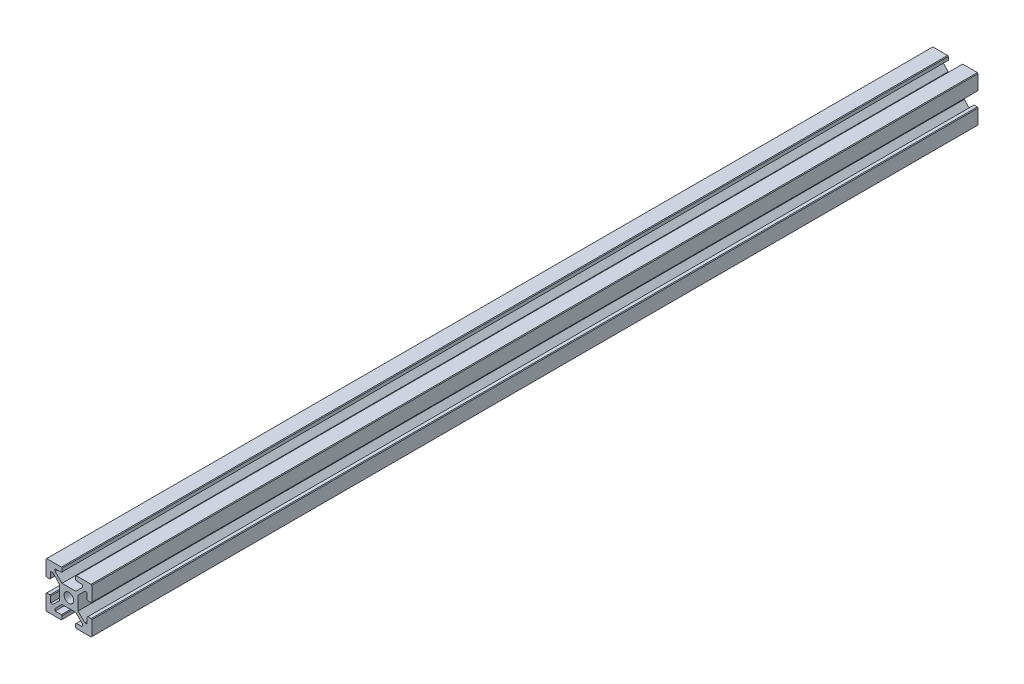
SolidWorks part; units mm, degrees
ref_plane "Front" through (0, 0, 0) normal (0, 0, 1) x (1, 0, 0)
ref_plane "Top" through (0, 0, 0) normal (0, 1, 0) x (1, 0, 0)
ref_plane "Right" through (0, 0, 0) normal (1, 0, 0) x (0, 0, -1)
sketch "Sketch1" plane through (0, 0, 0) normal (0, 0, 1) x (1, 0, 0)
  line L0 (-3, 10) -> (3, 10)
  line L1 (-10, 10) -> (10, 10)
  line L2 (-10, 10) -> (-10, -10)
  line L3 (-10, -10) -> (10, -10)
  line L4 (10, 10) -> (10, -10)
  line L5 (-10, 10) -> (10, -10) construction
  line L6 (-10, -10) -> (10, 10) construction
  line L7 (3, 10) -> (3, 8)
  line L8 (3, 8) -> (6, 8)
  line L9 (-3, 4) -> (3, 4)
  line L10 (0, -11) -> (0, 11) construction
  line L11 (3, 4) -> (6, 7)
  line L12 (6, 7) -> (6, 8)
  line L13 (10, 3) -> (10, -3)
  line L14 (-3, 10) -> (-3, 8)
  line L15 (-3, 8) -> (-6, 8)
  line L16 (-6, 7) -> (-6, 8)
  line L17 (-3, 4) -> (-6, 7)
  line L18 (10, -3) -> (8, -3)
  line L19 (8, -3) -> (8, -6)
  line L20 (7, -6) -> (8, -6)
  line L21 (4, -3) -> (7, -6)
  line L22 (4, 3) -> (4, -3)
  line L23 (4, 3) -> (7, 6)
  line L24 (7, 6) -> (8, 6)
  line L25 (8, 3) -> (8, 6)
  line L26 (10, 3) -> (8, 3)
  line L27 (3, -10) -> (-3, -10)
  line L28 (-3, -10) -> (-3, -8)
  line L29 (-3, -8) -> (-6, -8)
  line L30 (-6, -7) -> (-6, -8)
  line L31 (-3, -4) -> (-6, -7)
  line L32 (3, -4) -> (-3, -4)
  line L33 (3, -4) -> (6, -7)
  line L34 (6, -7) -> (6, -8)
  line L35 (3, -8) -> (6, -8)
  line L36 (3, -10) -> (3, -8)
  line L37 (-10, -3) -> (-10, 3)
  line L38 (-10, 3) -> (-8, 3)
  line L39 (-8, 3) -> (-8, 6)
  line L40 (-7, 6) -> (-8, 6)
  line L41 (-4, 3) -> (-7, 6)
  line L42 (-4, -3) -> (-4, 3)
  line L43 (-4, -3) -> (-7, -6)
  line L44 (-7, -6) -> (-8, -6)
  line L45 (-8, -3) -> (-8, -6)
  line L46 (-10, -3) -> (-8, -3)
  circle A0 centre (0, 0) radius 2.1
  point P0 (0, 0)
  point P18 (0, 10)
  point P22 (0, 4)
  point P53 (0, 0)
  dimension "D1" = 20
  dimension "D2" = 20
  dimension "D3" = 3
  dimension "D4" = 2
  dimension "D5" = 3
  dimension "D6" = 6
  dimension "D7" = 3
  dimension "D8" = 4
extrude "Boss-Extrude1" add sketch "Sketch1" along normal blind 387.35 contours L46 L2 L3 L28 L29 L30 L31 L32 L33 L34 L35 L36 L4 L18 L19 L20 L21 L22 L23 L24 L25 L26 L1 L7 L8 L12 L11 L9 L17 L16 L15 L14 L38 L39 L40 L41 L42 L43 L44 L45 A0
chamfer "Chamfer1" distance 0.2828 angle 45 20 edges at (-8, 3, 193.675) (-3, 8, 193.675) (-3, 10, 193.675) (-10, 3, 193.675) (-10, 10, 193.675) (-8, -3, 193.675) (-10, -3, 193.675) (-10, -10, 193.675) (-3, -10, 193.675) (-3, -8, 193.675) (3, -8, 193.675) (3, -10, 193.675) (8, -3, 193.675) (10, -10, 193.675) (10, -3, 193.675) (8, 3, 193.675) (10, 3, 193.675) (10, 10, 193.675) (3, 8, 193.675) (3, 10, 193.675)
